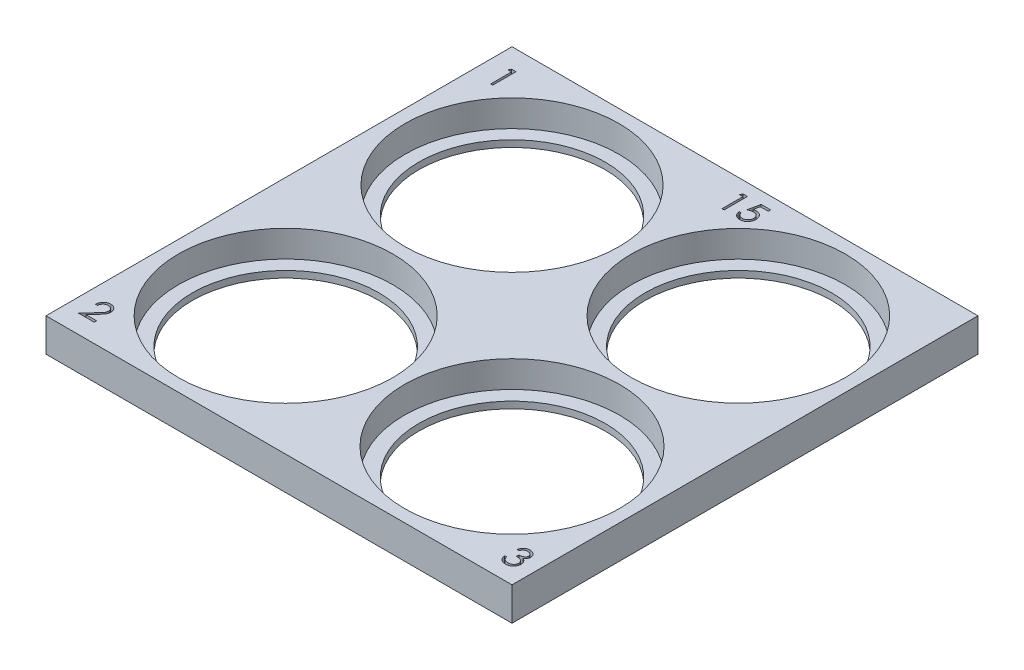
SolidWorks part; units mm, degrees
ref_plane "Front Plane" through (0, 0, 0) normal (0, 0, 1) x (1, 0, 0)
ref_plane "Top Plane" through (0, 0, 0) normal (0, 1, 0) x (1, 0, 0)
ref_plane "Right Plane" through (0, 0, 0) normal (1, 0, 0) x (0, 0, -1)
sketch "Sketch1" plane through (0, 0, 0) normal (0, 1, 0) x (1, 0, 0)
  line L1 (-16.618, 16.7109) -> (53.382, 16.7109)
  line L2 (-16.618, 16.7109) -> (-16.618, -53.2891)
  line L3 (-16.618, -53.2891) -> (53.382, -53.2891)
  line L4 (53.382, 16.7109) -> (53.382, -53.2891)
  dimension "D1" = 70
  dimension "D2" = 70
extrude "Boss-Extrude1" add sketch "Sketch1" along normal blind 5
sketch "Sketch2" plane through (0, 5, 0) normal (0, 1, 0) x (1, 0, 0)
  line L0 (-16.618, 16.7109) -> (-16.618, -53.2891) construction
  line L1 (53.382, 16.7109) -> (-16.618, 16.7109) construction
  line L2 (53.382, -53.2891) -> (53.382, 16.7109) construction
  line L3 (-16.618, -53.2891) -> (53.382, -53.2891) construction
  circle A0 centre (1.382, -1.2891) radius 16.05
  circle A1 centre (35.382, -1.2891) radius 16.075
  circle A2 centre (1.382, -35.2891) radius 16.1
  circle A3 centre (35.382, -35.2891) radius 16.15
  point P16 (0, 0)
  point P18 (0, 0)
  point P19 (0, 0)
  dimension "D1" = 18
  dimension "D3" = 18
  dimension "D5" = 18
  dimension "D2" = 18
  dimension "D4" = 18
  dimension "D6" = 18
  dimension "D7" = 18
  dimension "D8" = 18
extrude "Cut-Extrude1" cut sketch "Sketch2" against normal blind 4
sketch "Sketch3" plane through (0, 5, 0) normal (0, 1, 0) x (1, 0, 0)
  circle A0 centre (35.382, -1.2891) radius 14
  circle A1 centre (1.382, -35.2891) radius 14
  circle A2 centre (35.382, -35.2891) radius 14
  circle A3 centre (1.382, -1.2891) radius 14
extrude "Cut-Extrude2" cut sketch "Sketch3" against normal through all
sketch "Sketch4" plane through (0, 5, 0) normal (0, 1, 0) x (1, 0, 0)
  text T0 "1"
  text T1 "15\r\n"
  text T2 "2\r\n"
  text T3 "3\r\n"
  point P1 (-2.8435, 7.0613)
  point P2 (-13.7314, 10.3893)
  point P3 (-14.5942, 10.266)
  point P7 (48.8845, -50.994)
extrude "Cut-Extrude3" cut sketch "Sketch4" against normal blind 1
